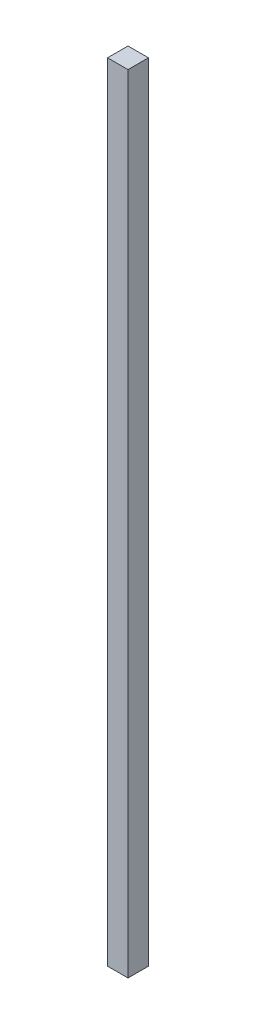
SolidWorks part; units mm, degrees
ref_plane "Front Plane" through (0, 0, 0) normal (0, 0, 1) x (1, 0, 0)
ref_plane "Top Plane" through (0, 0, 0) normal (0, 1, 0) x (1, 0, 0)
ref_plane "Right Plane" through (0, 0, 0) normal (1, 0, 0) x (0, 0, -1)
sketch "Sketch1" plane through (0, 0, 0) normal (0, 1, 0) x (1, 0, 0)
  line L1 (-6.35, -6.35) -> (6.35, -6.35)
  line L2 (-6.35, -6.35) -> (-6.35, 6.35)
  line L3 (-6.35, 6.35) -> (6.35, 6.35)
  line L4 (6.35, -6.35) -> (6.35, 6.35)
  line L5 (-6.35, -6.35) -> (6.35, 6.35) construction
  line L6 (-6.35, 6.35) -> (6.35, -6.35) construction
  point P0 (0, 0)
  dimension "D1" = 12.7
extrude "Boss-Extrude1" add sketch "Sketch1" along normal mid plane 488.95
